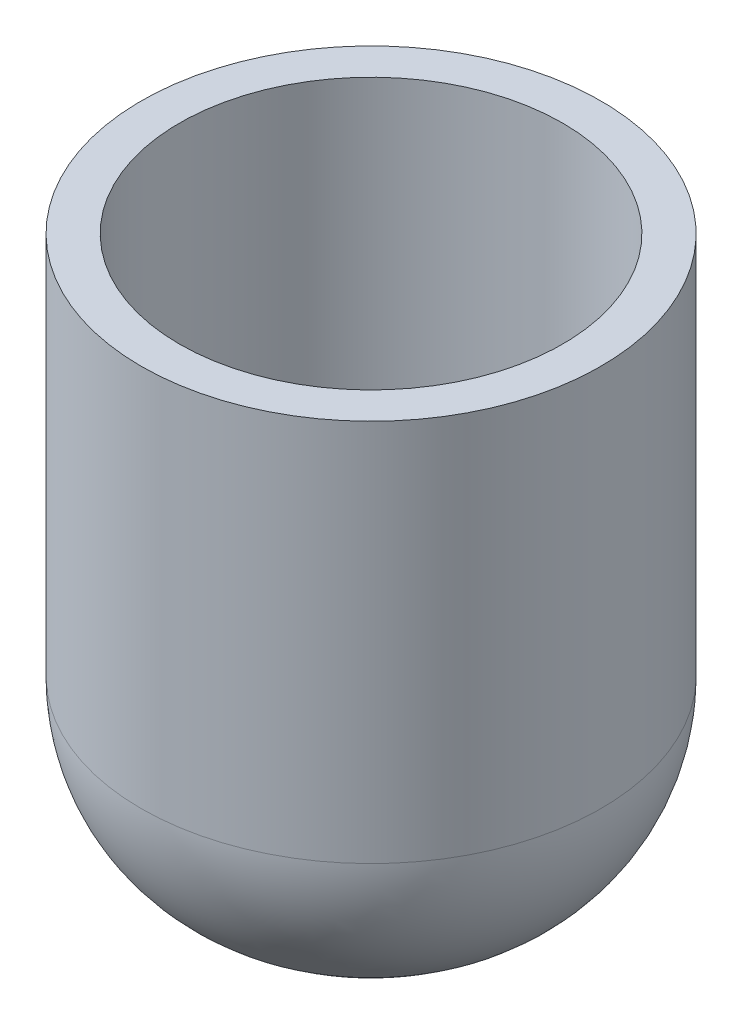
SolidWorks part; units mm, degrees
material "ABS PC"
ref_plane "Front Plane" through (0, 0, 0) normal (0, 0, 1) x (1, 0, 0)
ref_plane "Top Plane" through (0, 0, 0) normal (0, 1, 0) x (1, 0, 0)
ref_plane "Right Plane" through (0, 0, 0) normal (1, 0, 0) x (0, 0, -1)
sketch "Sketch1" plane through (0, 0, 0) normal (0, 1, 0) x (1, 0, 0)
  circle A0 centre (0, 0) radius 7.62
  dimension "D1" = 15.24
extrude "Boss-Extrude1" add sketch "Sketch1" against normal blind 19.05
fillet "Fillet1" radius 6.35 1 edges at (0, -19.05, 7.62)
shell "Shell1" thickness 1.27
